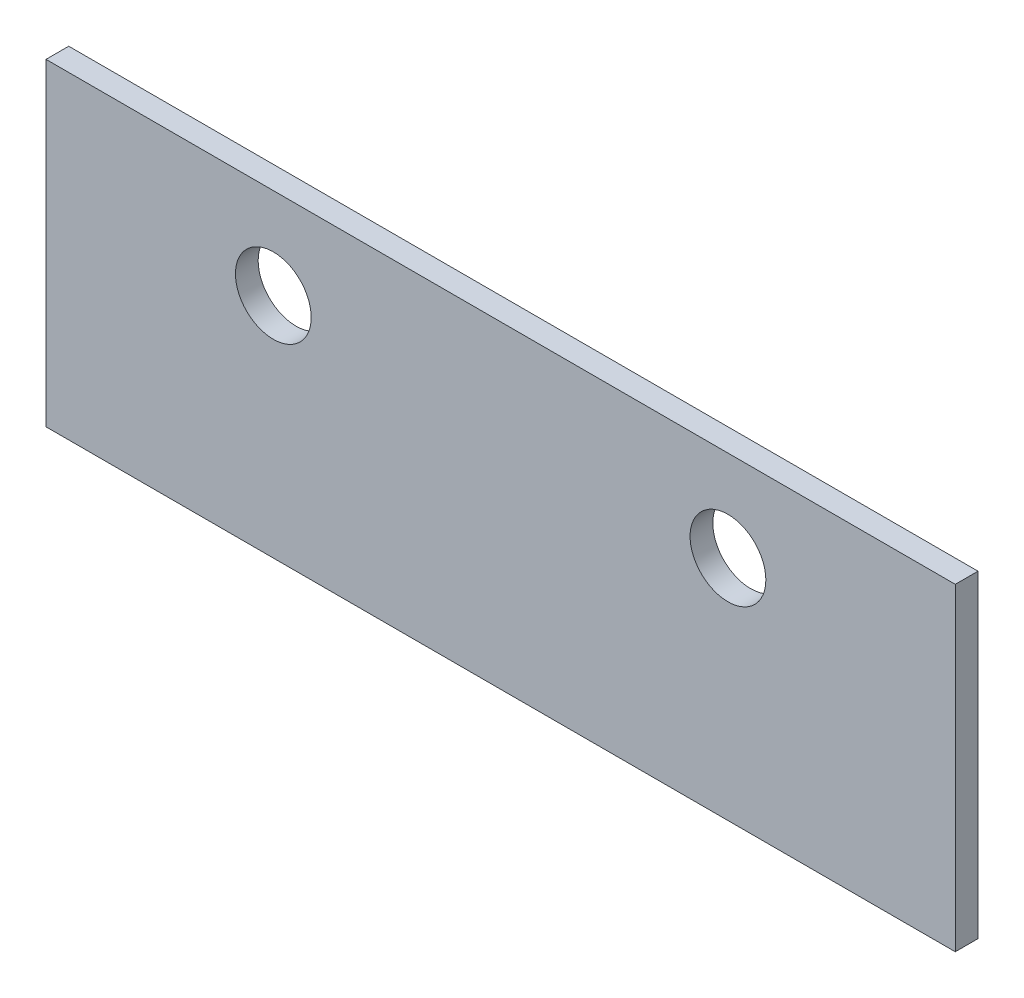
SolidWorks part; units mm, degrees
ref_plane "Plan1" through (0, 0, 0) normal (0, 0, 1) x (1, 0, 0)
ref_plane "Plan2" through (0, 0, 0) normal (0, 1, 0) x (1, 0, 0)
ref_plane "Plan3" through (0, 0, 0) normal (1, 0, 0) x (0, 0, -1)
sketch "Esquisse1" plane through (0, 0, 0) normal (0, 0, 1) x (1, 0, 0)
  line L1 (0, 0) -> (60, 0)
  line L2 (0, 0) -> (0, 21)
  line L3 (0, 21) -> (60, 21)
  line L4 (60, 0) -> (60, 21)
extrude "Base-Extrusion" add sketch "Esquisse1" along normal blind 1.5
sketch "Esquisse2" plane through (0, 0, 1.5) normal (0, 0, 1) x (1, 0, 0)
  circle A0 centre (15, 15) radius 2.5
  circle A1 centre (45, 15) radius 2.5
extrude "Enlèv. mat.-Extru.1" cut sketch "Esquisse2" against normal blind 2
